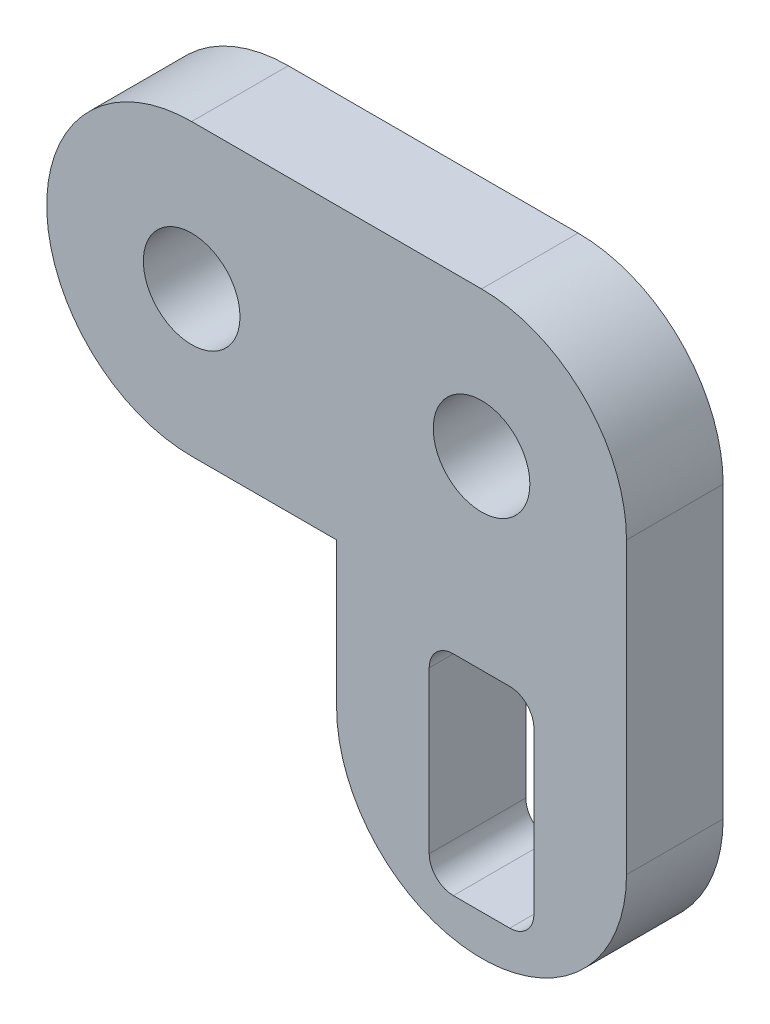
SolidWorks part; units mm, degrees
ref_plane "Alzado" through (0, 0, 0) normal (0, 0, 1) x (1, 0, 0)
ref_plane "Planta" through (0, 0, 0) normal (0, 1, 0) x (1, 0, 0)
ref_plane "Vista lateral" through (0, 0, 0) normal (1, 0, 0) x (0, 0, -1)
sketch "Model" plane through (0, 0, 0) normal (0, 0, 1) x (1, 0, 0)
  line L0 (149.3421, 211.824) -> (158.3421, 211.824)
  line L1 (153.8421, 202.824) -> (149.3421, 202.824)
  line L2 (162.8421, 198.324) -> (162.8421, 207.324)
  line L3 (153.8421, 198.324) -> (153.8421, 202.824)
  line L4 (156.7171, 195.824) -> (156.7171, 200.824)
  line L5 (157.4671, 201.574) -> (159.2171, 201.574)
  line L6 (159.9671, 200.824) -> (159.9671, 195.824)
  line L7 (159.2171, 195.074) -> (157.4671, 195.074)
  arc A0 (149.3421, 211.824) -> (149.3421, 202.824) centre (149.3421, 207.324) ccw
  arc A1 (162.8421, 207.324) -> (158.3421, 211.824) centre (158.3421, 207.324) ccw
  circle A2 centre (149.3421, 207.324) radius 1.5
  circle A3 centre (158.3421, 207.324) radius 1.5
  arc A4 (153.8421, 198.324) -> (162.8421, 198.324) centre (158.3421, 198.324) ccw
  arc A5 (157.4671, 201.574) -> (156.7171, 200.824) centre (157.4671, 200.824) ccw
  arc A6 (159.9671, 200.824) -> (159.2171, 201.574) centre (159.2171, 200.824) ccw
  arc A7 (159.2171, 195.074) -> (159.9671, 195.824) centre (159.2171, 195.824) ccw
  arc A8 (156.7171, 195.824) -> (157.4671, 195.074) centre (157.4671, 195.824) ccw
extrude "Saliente-Extruir1" add sketch "Model" along normal blind 3
